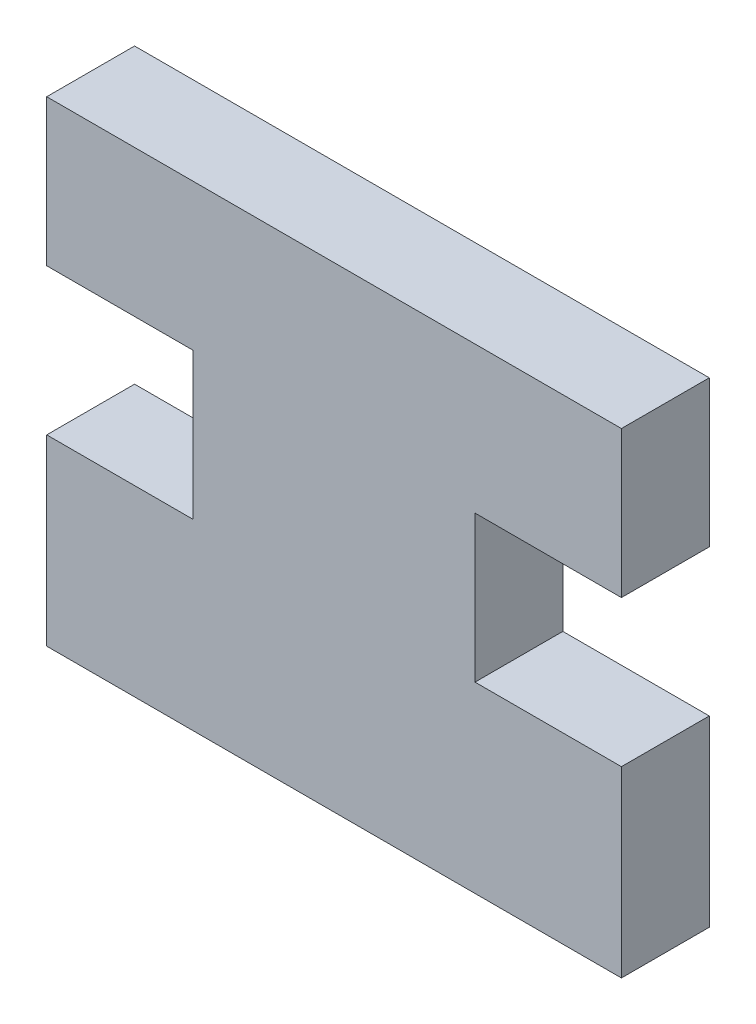
SolidWorks part; units mm, degrees
material "PBT General Purpose"
ref_plane "Front Plane" through (0, 0, 0) normal (0, 0, 1) x (1, 0, 0)
ref_plane "Top Plane" through (0, 0, 0) normal (0, 1, 0) x (1, 0, 0)
ref_plane "Right Plane" through (0, 0, 0) normal (1, 0, 0) x (0, 0, -1)
sketch "Sketch1" plane through (0, 0, 0) normal (0, 0, 1) x (1, 0, 0)
  line L0 (0, 0) -> (0, 0.5)
  line L1 (0, 0.5) -> (0.4, 0.5)
  line L2 (0.4, 0.5) -> (0.4, 0.9)
  line L3 (0.4, 0.9) -> (0, 0.9)
  line L4 (0, 0.9) -> (0, 1.3)
  line L5 (0, 1.3) -> (1.57, 1.3)
  line L6 (1.57, 1.3) -> (1.57, 0.9)
  line L7 (1.57, 0.9) -> (1.17, 0.9)
  line L8 (1.17, 0.9) -> (1.17, 0.5)
  line L9 (1.17, 0.5) -> (1.57, 0.5)
  line L10 (1.57, 0.5) -> (1.57, 0)
  line L11 (1.57, 0) -> (0, 0)
  point P11 (1.17, 0.4781)
  dimension "D1" = 0.4
  dimension "D2" = 0.4
  dimension "D3" = 0.77
  dimension "D4" = 0.4
  dimension "D5" = 0.4
  dimension "D6" = 0.5
  dimension "D7" = 0.4
extrude "Boss-Extrude1" add sketch "Sketch1" along normal blind 0.24
